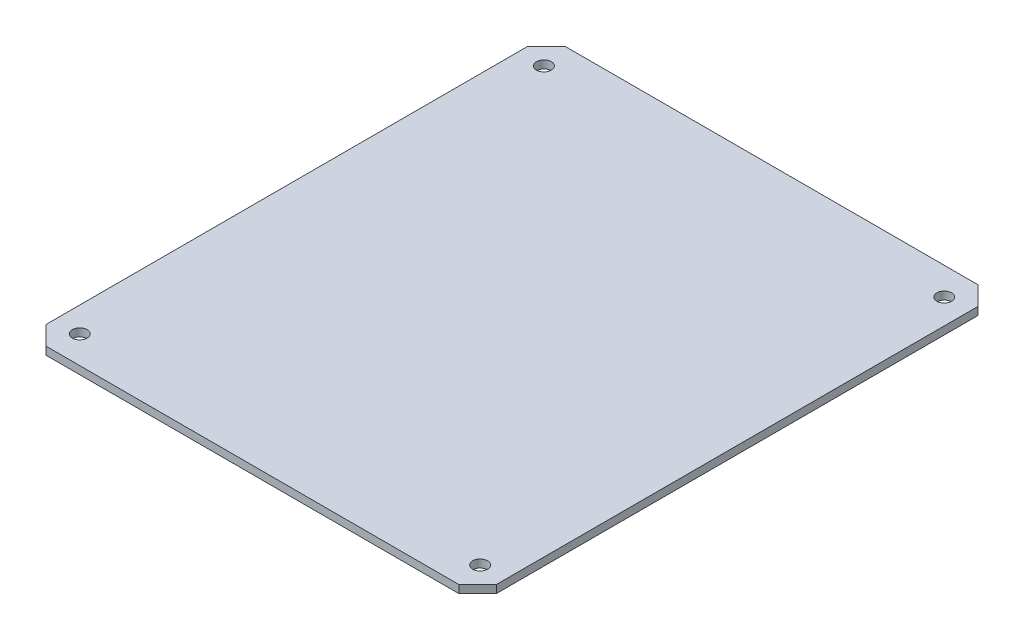
SolidWorks part; units mm, degrees
material "Circuit imprimé de calcul, complexe"
ref_plane "Plan de face" through (0, 0, 0) normal (0, 0, 1) x (1, 0, 0)
ref_plane "Plan de dessus" through (0, 0, 0) normal (0, 1, 0) x (1, 0, 0)
ref_plane "Plan de droite" through (0, 0, 0) normal (1, 0, 0) x (0, 0, -1)
sketch "Repères" plane through (0, 0, 0) normal (0, 1, 0) x (1, 0, 0)
  line L0 (-41.91, 52.705) -> (-45.72, 48.895)
  line L1 (-40.64, 47.117) -> (40.64, 47.117) construction
  line L2 (-40.64, 47.117) -> (-40.64, -47.117) construction
  line L3 (-40.64, -47.117) -> (40.64, -47.117) construction
  line L4 (40.64, 47.117) -> (40.64, -47.117) construction
  line L5 (-40.64, 47.117) -> (40.64, -47.117) construction
  line L6 (-40.64, -47.117) -> (40.64, 47.117) construction
  line L7 (-41.91, 52.705) -> (41.91, 52.705)
  line L8 (-45.72, 48.895) -> (-45.72, -48.895)
  line L9 (-41.91, -52.705) -> (41.91, -52.705)
  line L10 (45.72, 48.895) -> (45.72, -48.895)
  line L11 (-45.72, 52.705) -> (45.72, -52.705) construction
  line L12 (-45.72, -52.705) -> (45.72, 52.705) construction
  line L13 (41.91, 52.705) -> (45.72, 48.895)
  line L14 (45.72, -48.895) -> (41.91, -52.705)
  line L15 (-45.72, -48.895) -> (-41.91, -52.705)
  circle A0 centre (-40.64, 47.117) radius 1.5
  circle A1 centre (40.64, 47.117) radius 1.5
  circle A2 centre (40.64, -47.117) radius 1.5
  circle A3 centre (-40.64, -47.117) radius 1.5
  point P0 (0, 0)
  point P10 (0, 0)
  dimension "D1" = 3
  dimension "D2" = 81.28
  dimension "D3" = 94.234
  dimension "D4" = 91.44
  dimension "D5" = 105.41
extrude "CI" add sketch "Repères" along normal blind 1.6
